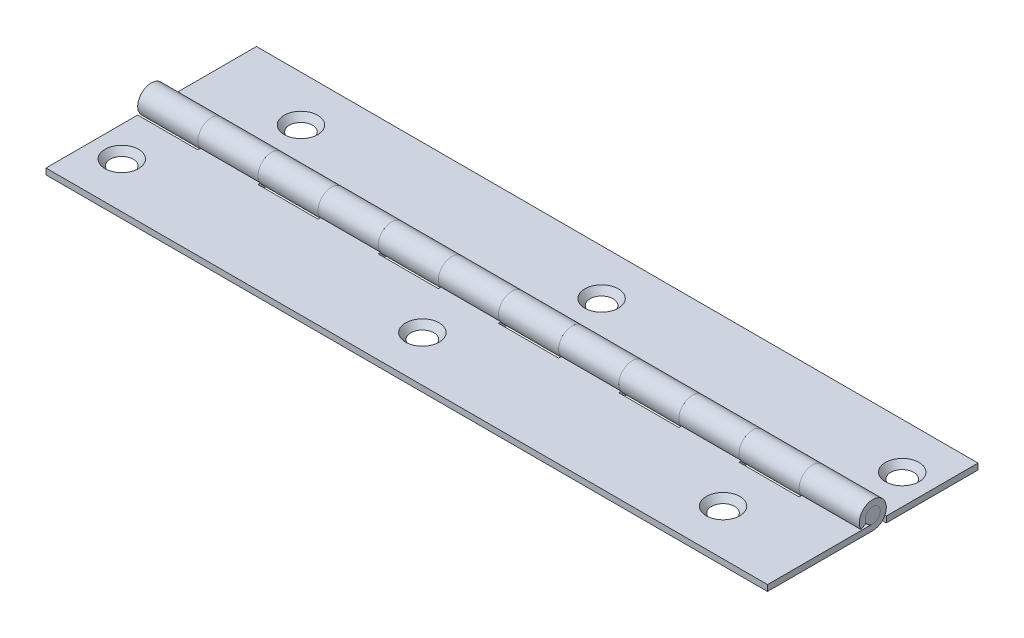
SolidWorks part; units mm, degrees
ref_plane "Front" through (0, 0, 0) normal (0, 0, 1) x (1, 0, 0)
ref_plane "Top" through (0, 0, 0) normal (0, 1, 0) x (1, 0, 0)
ref_plane "Right" through (0, 0, 0) normal (1, 0, 0) x (0, 0, -1)
sketch "Sketch1" plane through (0, 0, 0) normal (1, 0, 0) x (0, 0, -1)
  line L0 (-2.8575, -1.5875) -> (0, 0) construction
  line L1 (0, -1.5875) -> (-22.225, -1.5875)
  line L2 (-2.4979, -1.3877) -> (-1.3877, -0.771)
  line L3 (0, -2.8575) -> (-22.225, -2.8575)
  line L4 (-22.225, -1.5875) -> (-22.225, -2.8575)
  line L5 (-2.8575, 0) -> (-2.8575, -2.8575) construction
  line L6 (-22.225, -2.8575) -> (22.225, -2.8575) construction
  arc A0 (0, -1.5875) -> (-1.3877, -0.771) centre (0, 0) ccw
  arc A1 (0, -2.8575) -> (-2.4979, -1.3877) centre (0, 0) ccw
  dimension "Pin Dia" = 3.175
  dimension "Th" = 1.27
  dimension "Open Wd" = 44.45
extrude "Left Leaf" add sketch "Sketch1" along normal mid plane 152.4
sketch "Sketch2" plane through (0, 0, 0) normal (0, 1, 0) x (1, 0, 0)
  line L0 (76.2, 2.8575) -> (-76.2, 2.8575) construction
  line L2 (-50.8, 2.8575) -> (-38.1, 2.8575)
  line L3 (-50.8, 2.8575) -> (-50.8, -2.8575)
  line L4 (-50.8, -2.8575) -> (-38.1, -2.8575)
  line L5 (-38.1, 2.8575) -> (-38.1, -2.8575)
  line L9 (-76.2, -2.8575) -> (-63.5, -2.8575)
  line L10 (-76.2, -2.8575) -> (-76.2, 2.8575)
  line L11 (-76.2, 2.8575) -> (-63.5, 2.8575)
  line L12 (-63.5, -2.8575) -> (-63.5, 2.8575)
  line L13 (-76.2, -2.8575) -> (76.2, -2.8575) construction
  line L15 (50.8, 2.8575) -> (63.5, 2.8575)
  line L16 (50.8, 2.8575) -> (50.8, -2.8575)
  line L17 (50.8, -2.8575) -> (63.5, -2.8575)
  line L18 (-76.2, 0) -> (-76.2, -22.225) construction
  line L19 (63.5, 2.8575) -> (63.5, -2.8575)
  line L20 (-25.4, 2.8575) -> (-12.7, 2.8575)
  line L21 (-25.4, 2.8575) -> (-25.4, -2.8575)
  line L22 (-25.4, -2.8575) -> (-12.7, -2.8575)
  line L23 (-12.7, 2.8575) -> (-12.7, -2.8575)
  line L24 (0, 2.8575) -> (12.7, 2.8575)
  line L25 (0, 2.8575) -> (0, -2.8575)
  line L26 (0, -2.8575) -> (12.7, -2.8575)
  line L27 (12.7, 2.8575) -> (12.7, -2.8575)
  line L28 (25.4, 2.8575) -> (38.1, 2.8575)
  line L29 (25.4, 2.8575) -> (25.4, -2.8575)
  line L30 (25.4, -2.8575) -> (38.1, -2.8575)
  line L31 (38.1, 2.8575) -> (38.1, -2.8575)
  dimension "D1" = 12.7
  dimension "D2" = 12.7
  dimension "End Knuckle" = 12.7
  dimension "D3" = 12.7
  dimension "D4" = 12.7
  dimension "D5" = 12.7
extrude "Cut-Extrude1" cut sketch "Sketch2" against normal through all and the other way through all
sketch "Sketch3" plane through (0, 0, 0) normal (1, 0, 0) x (0, 0, -1)
  line L0 (0, 17.042) -> (0, -15.7543) construction
  line L1 (22.225, -1.5875) -> (22.225, -2.8575)
  line L2 (2.4979, -1.3877) -> (1.3877, -0.771)
  line L3 (0, -1.5875) -> (-22.225, -1.5875) construction
  line L8 (0, -2.8575) -> (-22.225, -2.8575) construction
  line L17 (22.225, -1.5875) -> (0, -1.5875)
  line L19 (0, -2.8575) -> (22.225, -2.8575)
  arc A0 (0, -2.8575) -> (-2.4979, -1.3877) centre (0, 0) ccw construction
  arc A1 (0, -1.5875) -> (-1.3877, -0.771) centre (0, 0) ccw construction
  arc A4 (2.4979, -1.3877) -> (0, -2.8575) centre (0, 0) ccw
  arc A5 (1.3877, -0.771) -> (0, -1.5875) centre (0, 0) ccw
extrude "Right Leaf" add sketch "Sketch3" along normal mid plane 152.4 separate body
sketch "Sketch9" plane through (0, 0, 0) normal (0, 1, 0) x (1, 0, 0)
  line L1 (-63.5, 2.8575) -> (-50.8, 2.8575)
  line L2 (-63.5, 2.8575) -> (-63.5, -2.8575)
  line L3 (-63.5, -2.8575) -> (-50.8, -2.8575)
  line L4 (-50.8, 2.8575) -> (-50.8, -2.8575)
  line L5 (-38.1, 2.8575) -> (-25.4, 2.8575)
  line L6 (-38.1, 2.8575) -> (-38.1, -2.8575)
  line L7 (-38.1, -2.8575) -> (-25.4, -2.8575)
  line L8 (-25.4, 2.8575) -> (-25.4, -2.8575)
  line L9 (-12.7, 2.8575) -> (0, 2.8575)
  line L10 (-12.7, 2.8575) -> (-12.7, -2.8575)
  line L11 (-12.7, -2.8575) -> (0, -2.8575)
  line L12 (0, 2.8575) -> (0, -2.8575)
  line L13 (12.7, 2.8575) -> (25.4, 2.8575)
  line L14 (12.7, 2.8575) -> (12.7, -2.8575)
  line L15 (12.7, -2.8575) -> (25.4, -2.8575)
  line L16 (25.4, 2.8575) -> (25.4, -2.8575)
  line L17 (38.1, 2.8575) -> (50.8, 2.8575)
  line L18 (38.1, 2.8575) -> (38.1, -2.8575)
  line L19 (38.1, -2.8575) -> (50.8, -2.8575)
  line L20 (50.8, 2.8575) -> (50.8, -2.8575)
  line L21 (63.5, 2.8575) -> (76.2, 2.8575)
  line L22 (63.5, 2.8575) -> (63.5, -2.8575)
  line L23 (63.5, -2.8575) -> (76.2, -2.8575)
  line L24 (76.2, 2.8575) -> (76.2, -2.8575)
extrude "Cut-Extrude2" cut sketch "Sketch9" against normal through all and the other way through all
sketch "Sketch10" plane through (0, 0, 0) normal (1, 0, 0) x (0, 0, -1)
  circle A0 centre (0, 0) radius 1.5875
  arc A1 (0, -1.5875) -> (-1.3877, -0.771) centre (0, 0) ccw construction
extrude "Extrude1" add sketch "Sketch10" along normal mid plane 152.4 separate body
sketch "Sketch11" plane through (0, -1.5875, 0) normal (0, 1, 0) x (-1, 0, 0)
  line L0 (-76.2, 22.225) -> (76.2, 22.225) construction
  line L1 (-76.2, 0) -> (-76.2, 22.225) construction
  line L2 (-76.2, -22.225) -> (-76.2, -2.8575) construction
  line L3 (-76.2, -22.225) -> (76.2, -22.225) construction
  line L4 (76.2, 2.8575) -> (76.2, 22.225) construction
  line L5 (76.2, -22.225) -> (76.2, 0) construction
  point P0 (69.85, 12.573)
  point P1 (57.15, -12.573)
  point P2 (6.35, 12.573)
  point P3 (-6.35, -12.573)
  point P4 (-57.15, 12.573)
  point P5 (-69.85, -12.573)
  dimension "D1" = 63.5
  dimension "Hole1" = 9.652
  dimension "D2" = 19.05
  dimension "D3" = 9.652
  dimension "Hole2" = 6.35
  dimension "D4" = 6.35
  dimension "D5" = 63.5
  dimension "D6" = 19.05
hole_wizard "CSK for #6 Flat Head Machine Screw1" positions "3DSketch1" profile "Sketch12" countersink size "#6" standard "Ansi Inch" end condition through all
sketch3d "3DSketch1"
  point P0 (-57.15, -1.5875, -12.573)
  point P3 (6.35, -1.5875, -12.573)
  point P6 (69.85, -1.5875, -12.573)
  point P9 (-69.85, -1.5875, 12.573)
  point P12 (-6.35, -1.5875, 12.573)
  point P15 (57.15, -1.5875, 12.573)
sketch "Sketch12" plane through (-57.15, -1.5875, -12.573) normal (1, 0, 0) x (0, 0, 1)
  line L0 (0, 0) -> (0, 1.27)
  line L1 (0, 1.27) -> (1.8986, 1.27)
  line L2 (1.8986, 1.27) -> (1.8986, 1.892)
  line L3 (1.8986, 1.892) -> (3.5433, 0)
  line L5 (3.5433, 0) -> (0, 0)
  line L6 (-1.8986, 1.892) -> (-3.5433, 0) construction
  line L11 (0, -6.35) -> (0, 107.95) construction
  dimension "Thru Hole Dia." = 3.7973
  dimension "Thru Hole Depth" = 1.27
  dimension "Near C'Sink Dia." = 7.0866
  dimension "Near C'Sink Angle" = 82
equation "\"D3@Sketch11\" = \"Hole1@Sketch11\""
